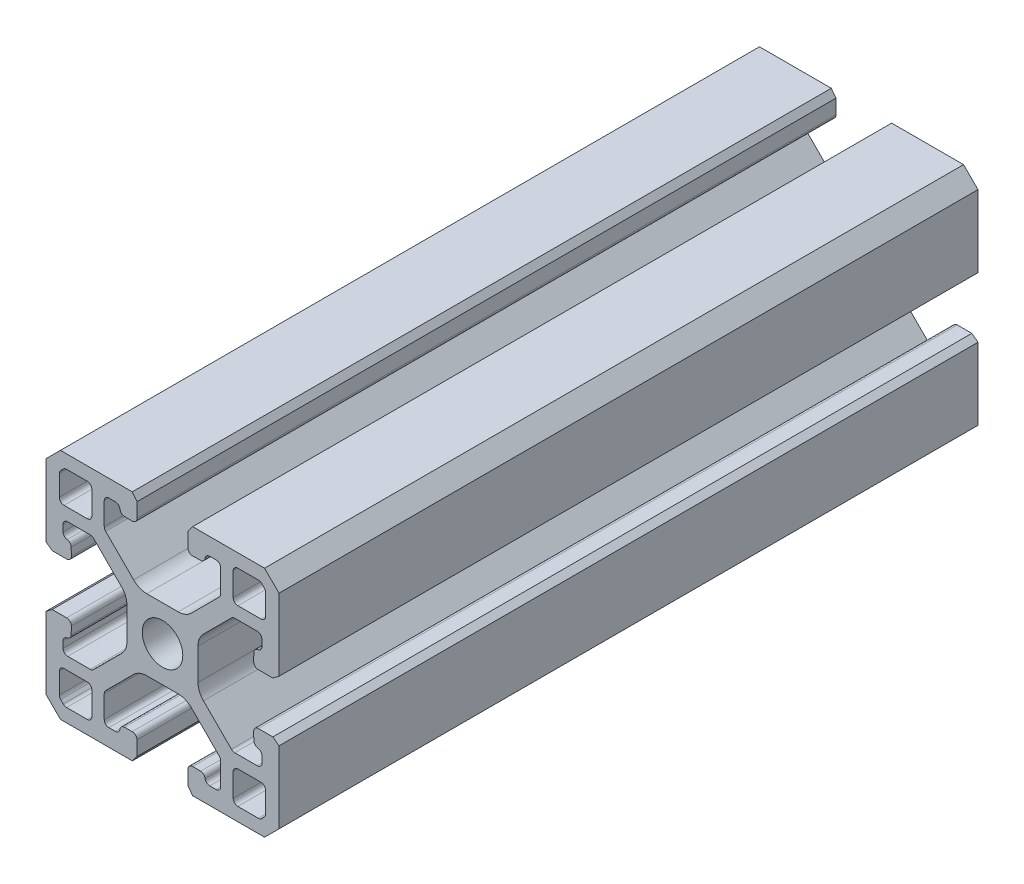
SolidWorks part; units mm, degrees
material "6063-T6"
ref_plane "Front Plane" through (0, 0, 0) normal (0, 0, 1) x (1, 0, 0)
ref_plane "Top Plane" through (0, 0, 0) normal (0, 1, 0) x (1, 0, 0)
ref_plane "Right Plane" through (0, 0, 0) normal (1, 0, 0) x (0, 0, -1)
sketch "Sketch1" plane through (0, 0, 0) normal (0, 0, 1) x (-1, 0, 0)
  line L0 (19.05, 0) -> (-19.05, 0) construction
  line L1 (0, -19.05) -> (0, 19.05) construction
  line L2 (-19.05, 4.9276) -> (-19.05, 16.6878)
  line L3 (-18.044, 4.1656) -> (-19.05, 4.9276)
  line L4 (-15.6692, 4.1656) -> (-18.044, 4.1656)
  line L5 (-14.9297, 6.2238) -> (-14.9074, 4.9409)
  line L6 (-16.256, 8.763) -> (-16.256, 7.7216)
  line L7 (-16.256, -7.7216) -> (-16.256, -8.763)
  line L8 (-14.9074, -4.9409) -> (-14.9297, -6.2238)
  line L9 (-18.044, -4.1656) -> (-15.6692, -4.1656)
  line L10 (-19.05, -4.9276) -> (-18.044, -4.1656)
  line L11 (-19.05, -16.6878) -> (-19.05, -4.9276)
  line L26 (-16.8656, 12.319) -> (-16.8656, 15.6829)
  line L27 (-16.6424, 16.2217) -> (-16.2217, 16.6424)
  line L28 (-15.6829, 16.8656) -> (-12.319, 16.8656)
  line L29 (-11.557, 16.1036) -> (-11.557, 12.319)
  line L30 (-12.319, 11.557) -> (-16.1036, 11.557)
  line L31 (-6.7001, -4.7245) -> (-11.2775, -9.3018)
  line L32 (-11.8163, -9.525) -> (-15.494, -9.525)
  line L34 (-15.494, 9.525) -> (-11.8163, 9.525)
  line L35 (-11.2775, 9.3018) -> (-6.7001, 4.7245)
  line L36 (-5.8074, 2.5692) -> (-5.8074, -2.5692)
  line L37 (-16.1036, -11.557) -> (-12.319, -11.557)
  line L38 (-11.557, -12.319) -> (-11.557, -16.1036)
  line L39 (-12.319, -16.8656) -> (-15.6829, -16.8656)
  line L40 (-16.2217, -16.6424) -> (-16.6424, -16.2217)
  line L41 (-16.8656, -15.6829) -> (-16.8656, -12.319)
  line L42 (15.6829, -16.8656) -> (12.319, -16.8656)
  line L43 (11.557, -16.1036) -> (11.557, -12.319)
  line L44 (12.319, -11.557) -> (16.1036, -11.557)
  line L45 (16.8656, -12.319) -> (16.8656, -15.6829)
  line L46 (16.6424, -16.2217) -> (16.2217, -16.6424)
  line L47 (11.557, 12.319) -> (11.557, 16.1036)
  line L48 (12.319, 16.8656) -> (15.6829, 16.8656)
  line L49 (16.2217, 16.6424) -> (16.6424, 16.2217)
  line L100 (5.8074, -2.5692) -> (5.8074, 2.5692)
  line L101 (6.7001, 4.7245) -> (11.2775, 9.3018)
  line L102 (11.8163, 9.525) -> (15.494, 9.525)
  line L103 (16.256, 8.763) -> (16.256, 7.7216)
  line L104 (14.9297, 6.2238) -> (14.9074, 4.9409)
  line L105 (15.6692, 4.1656) -> (18.044, 4.1656)
  line L106 (18.044, 4.1656) -> (19.05, 4.9276)
  line L107 (19.05, 4.9276) -> (19.05, 16.6878)
  line L108 (19.05, 16.6878) -> (16.6878, 19.05)
  line L109 (16.6878, 19.05) -> (4.9276, 19.05)
  line L110 (4.9276, 19.05) -> (4.1656, 18.044)
  line L111 (4.1656, 18.044) -> (4.1656, 15.6692)
  line L112 (4.9409, 14.9074) -> (6.2238, 14.9297)
  line L113 (7.7216, 16.256) -> (8.763, 16.256)
  line L114 (9.525, 15.494) -> (9.525, 11.8163)
  line L115 (9.3018, 11.2775) -> (4.7245, 6.7001)
  line L116 (2.5692, 5.8074) -> (-2.5692, 5.8074)
  line L117 (-4.7245, 6.7001) -> (-9.3018, 11.2775)
  line L118 (-9.525, 11.8163) -> (-9.525, 15.494)
  line L119 (-8.763, 16.256) -> (-7.7216, 16.256)
  line L120 (-6.2238, 14.9297) -> (-4.9409, 14.9074)
  line L121 (-4.1656, 15.6692) -> (-4.1656, 18.044)
  line L122 (-4.1656, 18.044) -> (-4.9276, 19.05)
  line L123 (-4.9276, 19.05) -> (-16.6878, 19.05)
  line L124 (-16.6878, 19.05) -> (-19.05, 16.6878)
  line L126 (-19.05, -16.6878) -> (-16.6878, -19.05)
  line L127 (-16.6878, -19.05) -> (-4.9276, -19.05)
  line L128 (-4.9276, -19.05) -> (-4.1656, -18.044)
  line L129 (-4.1656, -18.044) -> (-4.1656, -15.6692)
  line L130 (-4.9409, -14.9074) -> (-6.2238, -14.9297)
  line L131 (-7.7216, -16.256) -> (-8.763, -16.256)
  line L132 (-9.525, -15.494) -> (-9.525, -11.8163)
  line L133 (-9.3018, -11.2775) -> (-4.7245, -6.7001)
  line L134 (-2.5692, -5.8074) -> (2.5692, -5.8074)
  line L135 (4.7245, -6.7001) -> (9.3018, -11.2775)
  line L136 (9.525, -11.8163) -> (9.525, -15.494)
  line L137 (8.763, -16.256) -> (7.7216, -16.256)
  line L138 (6.2238, -14.9297) -> (4.9409, -14.9074)
  line L139 (4.1656, -15.6692) -> (4.1656, -18.044)
  line L140 (4.1656, -18.044) -> (4.9409, -19.05)
  line L141 (4.9409, -19.05) -> (16.6878, -19.05)
  line L142 (16.6878, -19.05) -> (19.05, -16.6878)
  line L143 (19.05, -16.6878) -> (19.05, -4.9276)
  line L144 (19.05, -4.9276) -> (18.044, -4.1656)
  line L145 (18.044, -4.1656) -> (15.6692, -4.1656)
  line L146 (14.9074, -4.9409) -> (14.9297, -6.2238)
  line L147 (16.256, -7.7216) -> (16.256, -8.763)
  line L148 (15.494, -9.525) -> (11.8163, -9.525)
  line L149 (11.2775, -9.3018) -> (6.7001, -4.7245)
  line L150 (16.8656, 15.6829) -> (16.8656, 12.319)
  line L151 (16.1036, 11.557) -> (12.319, 11.557)
  arc A0 (-16.256, 8.763) -> (-15.494, 9.525) centre (-15.494, 8.763) cw
  arc A1 (-14.9074, 4.9409) -> (-15.6692, 4.1656) centre (-15.6692, 4.9276) cw
  arc A2 (-15.5928, 6.966) -> (-14.9297, 6.2238) centre (-15.6916, 6.2105) cw
  arc A3 (-15.5928, 6.966) -> (-16.256, 7.7216) centre (-15.494, 7.7216) cw
  arc A4 (-15.494, -9.525) -> (-16.256, -8.763) centre (-15.494, -8.763) cw
  arc A5 (-16.256, -7.7216) -> (-15.5928, -6.966) centre (-15.494, -7.7216) cw
  arc A6 (-14.9297, -6.2238) -> (-15.5928, -6.966) centre (-15.6916, -6.2105) cw
  arc A7 (-15.6692, -4.1656) -> (-14.9074, -4.9409) centre (-15.6692, -4.9276) cw
  arc A27 (-16.6424, 16.2217) -> (-16.8656, 15.6829) centre (-16.1036, 15.6829) ccw
  arc A28 (-15.6829, 16.8656) -> (-16.2217, 16.6424) centre (-15.6829, 16.1036) ccw
  arc A29 (-11.557, 16.1036) -> (-12.319, 16.8656) centre (-12.319, 16.1036) ccw
  arc A30 (-12.319, 11.557) -> (-11.557, 12.319) centre (-12.319, 12.319) ccw
  arc A31 (-16.8656, 12.319) -> (-16.1036, 11.557) centre (-16.1036, 12.319) ccw
  arc A32 (-11.8163, -9.525) -> (-11.2775, -9.3018) centre (-11.8163, -8.763) ccw
  arc A35 (-11.2775, 9.3018) -> (-11.8163, 9.525) centre (-11.8163, 8.763) ccw
  arc A72 (5.8074, -2.5692) -> (6.7001, -4.7245) centre (8.8554, -2.5692) ccw
  arc A73 (6.7001, 4.7245) -> (5.8074, 2.5692) centre (8.8554, 2.5692) ccw
  arc A74 (11.8163, 9.525) -> (11.2775, 9.3018) centre (11.8163, 8.763) ccw
  arc A75 (16.256, 8.763) -> (15.494, 9.525) centre (15.494, 8.763) ccw
  arc A76 (15.5928, 6.966) -> (16.256, 7.7216) centre (15.494, 7.7216) ccw
  arc A77 (15.5928, 6.966) -> (14.9297, 6.2238) centre (15.6916, 6.2105) ccw
  arc A78 (14.9074, 4.9409) -> (15.6692, 4.1656) centre (15.6692, 4.9276) ccw
  arc A79 (4.1656, 15.6692) -> (4.9409, 14.9074) centre (4.9276, 15.6692) ccw
  arc A80 (6.2238, 14.9297) -> (6.966, 15.5928) centre (6.2105, 15.6916) ccw
  arc A81 (7.7216, 16.256) -> (6.966, 15.5928) centre (7.7216, 15.494) ccw
  arc A82 (9.525, 15.494) -> (8.763, 16.256) centre (8.763, 15.494) ccw
  arc A83 (9.3018, 11.2775) -> (9.525, 11.8163) centre (8.763, 11.8163) ccw
  arc A84 (2.5692, 5.8074) -> (4.7245, 6.7001) centre (2.5692, 8.8554) ccw
  arc A85 (-4.7245, 6.7001) -> (-2.5692, 5.8074) centre (-2.5692, 8.8554) ccw
  arc A86 (-9.525, 11.8163) -> (-9.3018, 11.2775) centre (-8.763, 11.8163) ccw
  arc A87 (-8.763, 16.256) -> (-9.525, 15.494) centre (-8.763, 15.494) ccw
  arc A88 (-6.966, 15.5928) -> (-7.7216, 16.256) centre (-7.7216, 15.494) ccw
  arc A89 (-6.966, 15.5928) -> (-6.2238, 14.9297) centre (-6.2105, 15.6916) ccw
  arc A90 (-4.9409, 14.9074) -> (-4.1656, 15.6692) centre (-4.9276, 15.6692) ccw
  arc A91 (-4.1656, -15.6692) -> (-4.9409, -14.9074) centre (-4.9276, -15.6692) ccw
  arc A92 (-6.2238, -14.9297) -> (-6.966, -15.5928) centre (-6.2105, -15.6916) ccw
  arc A93 (-7.7216, -16.256) -> (-6.966, -15.5928) centre (-7.7216, -15.494) ccw
  arc A94 (-9.525, -15.494) -> (-8.763, -16.256) centre (-8.763, -15.494) ccw
  arc A95 (-9.3018, -11.2775) -> (-9.525, -11.8163) centre (-8.763, -11.8163) ccw
  arc A96 (-2.5692, -5.8074) -> (-4.7245, -6.7001) centre (-2.5692, -8.8554) ccw
  arc A97 (4.7245, -6.7001) -> (2.5692, -5.8074) centre (2.5692, -8.8554) ccw
  arc A98 (9.525, -11.8163) -> (9.3018, -11.2775) centre (8.763, -11.8163) ccw
  arc A99 (8.763, -16.256) -> (9.525, -15.494) centre (8.763, -15.494) ccw
  arc A100 (6.966, -15.5928) -> (7.7216, -16.256) centre (7.7216, -15.494) ccw
  arc A101 (6.966, -15.5928) -> (6.2238, -14.9297) centre (6.2105, -15.6916) ccw
  arc A102 (4.9409, -14.9074) -> (4.1656, -15.6692) centre (4.9276, -15.6692) ccw
  arc A103 (15.6692, -4.1656) -> (14.9074, -4.9409) centre (15.6692, -4.9276) ccw
  arc A104 (14.9297, -6.2238) -> (15.5928, -6.966) centre (15.6916, -6.2105) ccw
  arc A105 (16.256, -7.7216) -> (15.5928, -6.966) centre (15.494, -7.7216) ccw
  arc A106 (15.494, -9.525) -> (16.256, -8.763) centre (15.494, -8.763) ccw
  arc A107 (11.2775, -9.3018) -> (11.8163, -9.525) centre (11.8163, -8.763) ccw
  arc A108 (-5.8074, 2.5692) -> (-6.7001, 4.7245) centre (-8.8554, 2.5692) ccw
  arc A109 (-6.7001, -4.7245) -> (-5.8074, -2.5692) centre (-8.8554, -2.5692) ccw
  arc A110 (-11.557, -12.319) -> (-12.319, -11.557) centre (-12.319, -12.319) ccw
  arc A111 (-12.319, -16.8656) -> (-11.557, -16.1036) centre (-12.319, -16.1036) ccw
  arc A112 (-16.2217, -16.6424) -> (-15.6829, -16.8656) centre (-15.6829, -16.1036) ccw
  arc A113 (-16.8656, -15.6829) -> (-16.6424, -16.2217) centre (-16.1036, -15.6829) ccw
  arc A114 (-16.1036, -11.557) -> (-16.8656, -12.319) centre (-16.1036, -12.319) ccw
  circle A115 centre (0, 0) radius 3.3147
  arc A116 (11.557, -16.1036) -> (12.319, -16.8656) centre (12.319, -16.1036) ccw
  arc A117 (12.319, -11.557) -> (11.557, -12.319) centre (12.319, -12.319) ccw
  arc A118 (16.8656, -12.319) -> (16.1036, -11.557) centre (16.1036, -12.319) ccw
  arc A119 (16.6424, -16.2217) -> (16.8656, -15.6829) centre (16.1036, -15.6829) ccw
  arc A120 (15.6829, -16.8656) -> (16.2217, -16.6424) centre (15.6829, -16.1036) ccw
  arc A121 (12.319, 16.8656) -> (11.557, 16.1036) centre (12.319, 16.1036) ccw
  arc A122 (16.2217, 16.6424) -> (15.6829, 16.8656) centre (15.6829, 16.1036) ccw
  arc A123 (16.8656, 15.6829) -> (16.6424, 16.2217) centre (16.1036, 15.6829) ccw
  arc A124 (16.1036, 11.557) -> (16.8656, 12.319) centre (16.1036, 12.319) ccw
  arc A125 (11.557, 12.319) -> (12.319, 11.557) centre (12.319, 12.319) ccw
  dimension "D1" = 6.6294
  dimension "D2" = 38.1
  dimension "D3" = 38.1
extrude "Boss-Extrude1" add sketch "Sketch1" along normal blind 114.3
